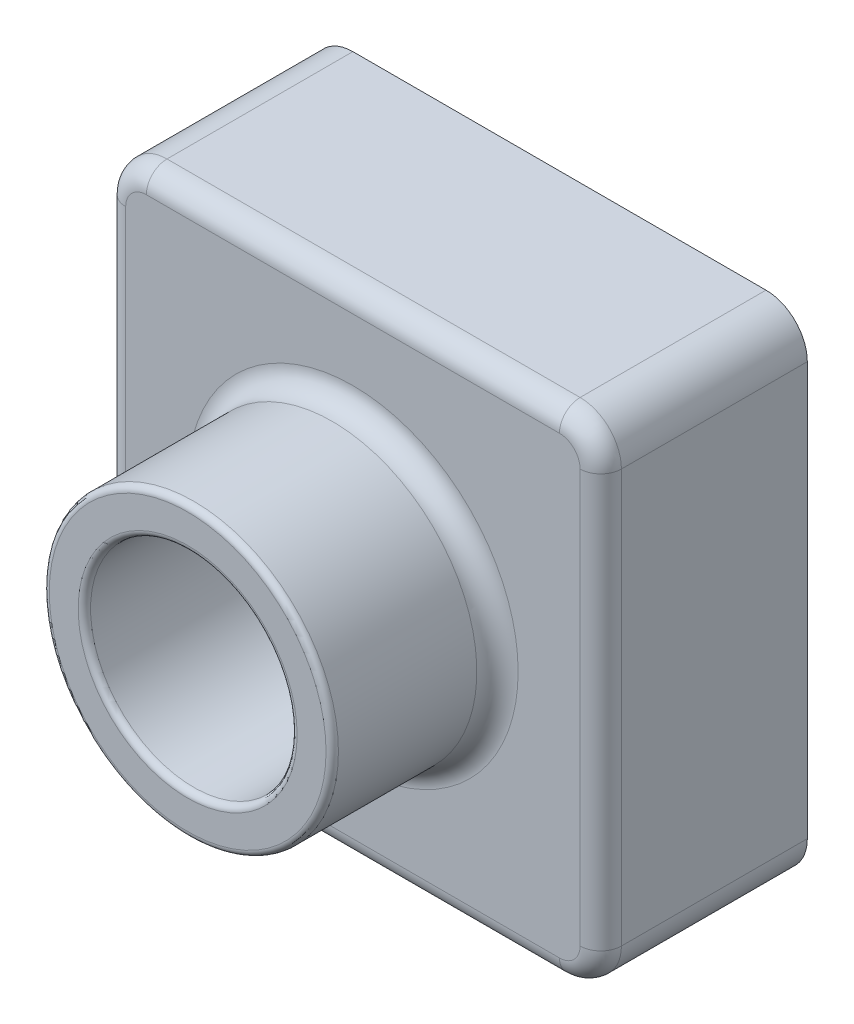
SolidWorks part; units mm, degrees
material "Chrome Stainless Steel"
ref_plane "Front Plane" through (0, 0, 0) normal (0, 0, 1) x (1, 0, 0)
ref_plane "Top Plane" through (0, 0, 0) normal (0, 1, 0) x (1, 0, 0)
ref_plane "Right Plane" through (0, 0, 0) normal (1, 0, 0) x (0, 0, -1)
sketch "Sketch1" plane through (0, 0, 0) normal (0, 0, 1) x (1, 0, 0)
  line L1 (0, 0) -> (120, 0)
  line L2 (0, 0) -> (0, 120)
  line L3 (0, 120) -> (120, 120)
  line L4 (120, 0) -> (120, 120)
  dimension "D1" = 120
  dimension "D2" = 120
extrude "Boss-Extrude1" add sketch "Sketch1" along normal blind 50 contours L3 L4 L1 L2
sketch "Sketch2" plane through (0, 0, 50) normal (0, 0, 1) x (1, 0, 0)
  line L0 (0, 120) -> (120, 120) construction
  line L1 (120, 0) -> (120, 120) construction
  circle A0 centre (60, 60) radius 35
  dimension "D1" = 70
  dimension "D2" = 60
  dimension "D3" = 60
extrude "Boss-Extrude2" add sketch "Sketch2" along normal blind 40
sketch "Sketch3" plane through (0, 0, 90) normal (0, 0, 1) x (1, 0, 0)
  circle A0 centre (60, 60) radius 25
  dimension "D1" = 50
extrude "Cut-Extrude1" cut sketch "Sketch3" against normal through all
fillet "Fillet1" radius 10 4 edges at (0, 120, 25) (0, 0, 25) (120, 0, 25) (120, 120, 25)
fillet "Fillet2" radius 1.5 2 edges at (95, 60, 90) (85, 60, 90)
fillet "Fillet3" radius 5 9 edges at (117.0711, 117.0711, 50) (120, 60, 50) (117.0711, 2.9289, 50) (60, 0, 50) (2.9289, 2.9289, 50) (0, 60, 50) (2.9289, 117.0711, 50) (60, 120, 50) (95, 60, 50)
shell "Shell1" thickness 2
